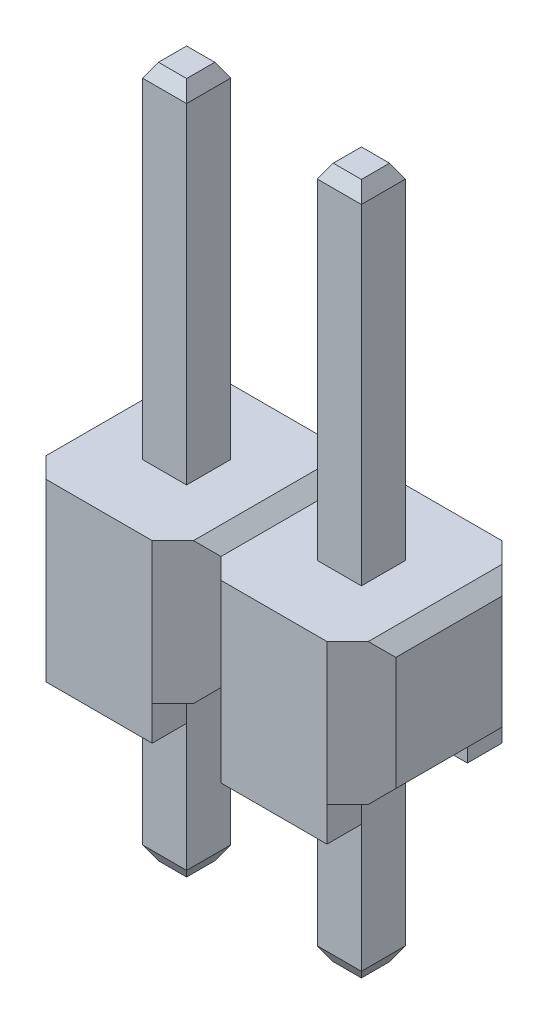
SolidWorks part; units mm, degrees
ref_plane "Front Plane" through (0, 0, 0) normal (0, 0, 1) x (1, 0, 0)
ref_plane "Top Plane" through (0, 0, 0) normal (0, 1, 0) x (1, 0, 0)
ref_plane "Right Plane" through (0, 0, 0) normal (1, 0, 0) x (0, 0, -1)
sketch "Sketch1" plane through (0, 0, 0) normal (0, 1, 0) x (1, 0, 0)
  line L0 (-2.04, -1.27) -> (-0.5, -1.27)
  line L1 (0, -0.77) -> (-0.5, -1.27)
  line L2 (0.5, -1.27) -> (2.04, -1.27)
  line L3 (-2.794, 0) -> (2.794, 0) construction
  line L4 (-2.54, 0) -> (-1.59, 0) construction
  line L5 (-1.59, 0) -> (-0.95, 0) construction
  line L6 (-0.95, 0) -> (0.95, 0) construction
  line L7 (0.95, 0) -> (1.59, 0) construction
  line L8 (1.59, 0) -> (2.54, 0) construction
  line L9 (-1.27, 1.27) -> (-1.27, 0.32) construction
  line L10 (-1.27, 0.32) -> (-1.27, -0.32) construction
  line L11 (-1.27, -0.32) -> (-1.27, -1.27) construction
  line L12 (0, 0.77) -> (0, 0) construction
  line L13 (0, 0) -> (0, -0.77) construction
  line L22 (1.59, -0.32) -> (1.59, 0.32)
  line L34 (0, -1.397) -> (0, 1.397) construction
  line L44 (-2.04, 1.27) -> (-0.5, 1.27)
  line L45 (-0.5, 1.27) -> (0, 0.77)
  line L46 (-1.59, -0.32) -> (-1.59, 0.32)
  line L47 (0.95, -0.32) -> (1.59, -0.32)
  line L48 (2.54, 0.77) -> (2.54, -0.77)
  line L49 (-2.04, -1.27) -> (-2.54, -0.77)
  line L51 (-1.59, -0.32) -> (-0.95, -0.32)
  line L53 (0, 0.77) -> (0.5, 1.27)
  line L54 (2.54, -0.77) -> (2.04, -1.27)
  line L55 (2.04, 1.27) -> (2.54, 0.77)
  line L56 (0.95, 0.32) -> (1.59, 0.32)
  line L57 (-2.54, 0.77) -> (-2.04, 1.27)
  line L58 (-2.54, -0.77) -> (-2.54, 0.77)
  line L59 (-1.59, 0.32) -> (-0.95, 0.32)
  line L60 (-0.95, -0.32) -> (-0.95, 0.32)
  line L61 (0.5, -1.27) -> (0, -0.77)
  line L62 (0.5, 1.27) -> (2.04, 1.27)
  line L63 (0.95, -0.32) -> (0.95, 0.32)
  dimension "D1" = 5.08
  dimension "D2" = 2.54
  dimension "D3" = 1.27
  dimension "D4" = 2.54
  dimension "D5" = 0.64
  dimension "D7" = 0.5
  dimension "D10" = 0.5
  dimension "D11" = 1.54
extrude "Boss-Extrude1" add sketch "Sketch1" against normal blind 2.05
sketch "Sketch2" plane through (0, 0, 0) normal (0, 0, 1) x (1, 0, 0)
  line L0 (-2.54, -0.2) -> (-2.54, 0)
  line L3 (-2.54, -2.05) -> (-2.54, 0) construction
  line L4 (-2.54, 0) -> (-2.34, 0)
  line L5 (-2.54, 0) -> (-2.04, 0) construction
  line L8 (-2.34, 0) -> (-2.54, -0.2)
  line L10 (-0.2, 0) -> (0.2, 0)
  line L11 (-0.5, 0) -> (0, 0) construction
  line L13 (0, 0) -> (0.5, 0) construction
  line L15 (0.2, 0) -> (0, -0.2)
  line L16 (0, -2.05) -> (0, 0) construction
  line L17 (0, -0.2) -> (-0.2, 0)
  line L18 (2.34, 0) -> (2.54, 0)
  line L19 (2.04, 0) -> (2.54, 0) construction
  line L20 (2.54, 0) -> (2.54, -0.2)
  line L21 (2.54, -2.05) -> (2.54, 0) construction
  line L22 (2.54, -0.2) -> (2.34, 0)
  line L23 (-2.54, -1.85) -> (-2.34, -2.05)
  line L24 (-2.54, -2.05) -> (-2.04, -2.05) construction
  line L25 (-2.34, -2.05) -> (-2.54, -2.05)
  line L26 (-2.54, -2.05) -> (-2.54, -1.85)
  line L27 (-0.2, -2.05) -> (0, -1.85)
  line L28 (-0.5, -2.05) -> (0, -2.05) construction
  line L29 (0, -1.85) -> (0.2, -2.05)
  line L31 (0.2, -2.05) -> (-0.2, -2.05)
  line L32 (2.34, -2.05) -> (2.54, -1.85)
  line L34 (2.54, -1.85) -> (2.54, -2.05)
  line L35 (2.54, -2.05) -> (2.34, -2.05)
  dimension "D1" = 0.2
  dimension "D2" = 0.4
extrude "Cut-Extrude1" cut sketch "Sketch2" against normal mid plane 10
sketch "Sketch3" plane through (0, -2.05, 0) normal (0, -1, 0) x (1, 0, 0)
  line L2 (-2.04, -1.27) -> (-0.5, -1.27)
  line L3 (-2.04, -1.27) -> (-2.04, -0.77)
  line L4 (-2.04, -0.77) -> (-0.5, -0.77)
  line L5 (-0.5, -1.27) -> (-0.5, -0.77)
  line L6 (-0.5, 1.27) -> (-2.04, 1.27)
  line L7 (-0.5, 1.27) -> (-0.5, 0.77)
  line L8 (-0.5, 0.77) -> (-2.04, 0.77)
  line L9 (-2.04, 1.27) -> (-2.04, 0.77)
  line L10 (0.5, 1.27) -> (2.04, 1.27)
  line L11 (0.5, 1.27) -> (0.5, 0.77)
  line L12 (0.5, 0.77) -> (2.04, 0.77)
  line L13 (2.04, 1.27) -> (2.04, 0.77)
  line L14 (2.04, -1.27) -> (0.5, -1.27)
  line L15 (2.04, -1.27) -> (2.04, -0.77)
  line L16 (2.04, -0.77) -> (0.5, -0.77)
  line L17 (0.5, -1.27) -> (0.5, -0.77)
  dimension "D1" = 0.5
extrude "Boss-Extrude2" add sketch "Sketch3" along normal blind 0.5
sketch "Sketch4" plane through (0, 0, 0) normal (0, 1, 0) x (1, 0, 0)
  line L1 (-1.59, 0.32) -> (-0.95, 0.32)
  line L2 (-1.59, 0.32) -> (-1.59, -0.32)
  line L3 (-1.59, -0.32) -> (-0.95, -0.32)
  line L4 (-0.95, 0.32) -> (-0.95, -0.32)
  line L5 (0.95, 0.32) -> (1.59, 0.32)
  line L6 (0.95, 0.32) -> (0.95, -0.32)
  line L7 (0.95, -0.32) -> (1.59, -0.32)
  line L8 (1.59, 0.32) -> (1.59, -0.32)
extrude "Boss-Extrude3" add sketch "Sketch4" along normal blind 5 and the other way offset from surface (5.05 mm away) 3 other way up to face at (1.27, -2.05, 0)
chamfer "Chamfer1" distance 0.2 angle 30 16 edges at (-1.27, -5.05, 0.32) (-0.95, -5.05, 0) (-1.27, -5.05, -0.32) (-1.59, -5.05, 0) (1.27, -5.05, 0.32) (1.59, -5.05, 0) (1.27, -5.05, -0.32) (0.95, -5.05, 0) (1.27, 5, -0.32) (1.59, 5, 0) (1.27, 5, 0.32) (0.95, 5, 0) (-1.27, 5, -0.32) (-0.95, 5, 0) (-1.27, 5, 0.32) (-1.59, 5, 0)
sketch "Sketch5" plane through (0, -5.05, 0) normal (0, -1, 0) x (1, 0, 0)
  line L0 (-1.59, 0) -> (-0.95, 0) construction
  line L1 (-1.59, -0.32) -> (-1.59, 0.32) construction
  line L2 (-0.95, 0.32) -> (-0.95, -0.32) construction
  circle A0 centre (-1.27, 0) radius 0.125
  dimension "D1" = 0.25
extrude "Cut-Extrude2" cut sketch "Sketch5" against normal blind 1
